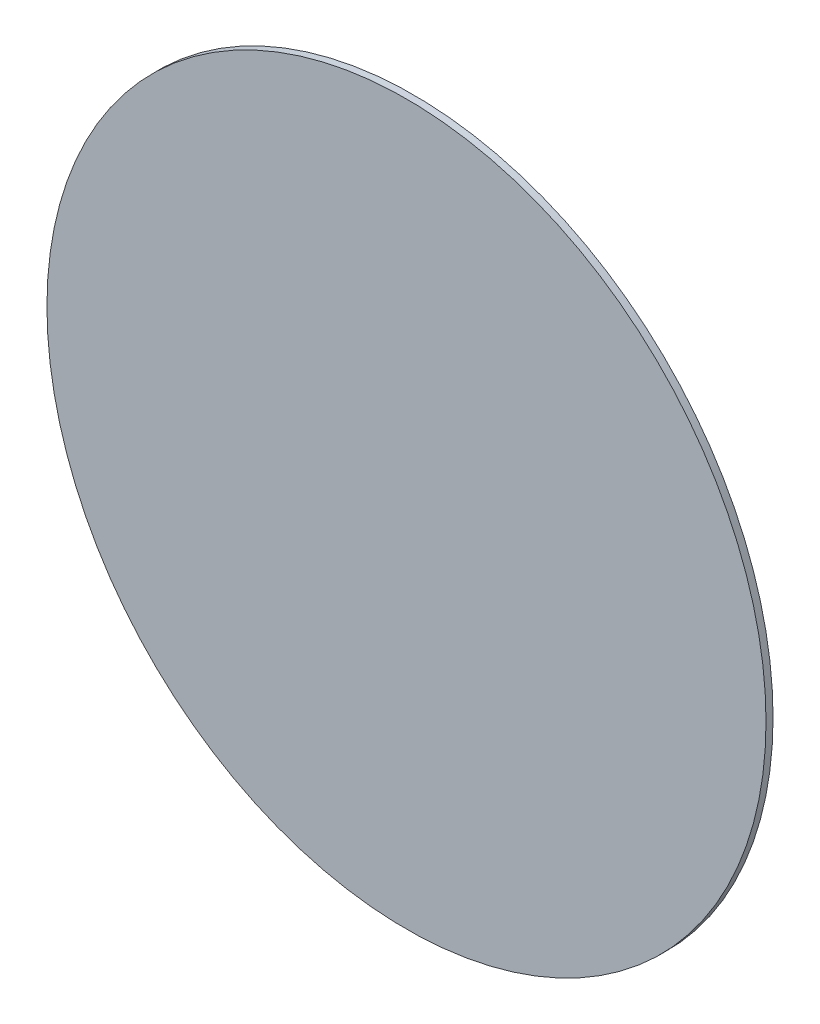
SolidWorks part; units mm, degrees
ref_plane "Plan de face" through (0, 0, 0) normal (0, 0, 1) x (1, 0, 0)
ref_plane "Plan de dessus" through (0, 0, 0) normal (0, 1, 0) x (1, 0, 0)
ref_plane "Plan de droite" through (0, 0, 0) normal (1, 0, 0) x (0, 0, -1)
sketch "Esquisse1" plane through (0, 0, 0) normal (0, 0, 1) x (1, 0, 0)
  circle A0 centre (0, 0) radius 13.3
  dimension "D1" = 26.6
extrude "Boss.-Extru.1" add sketch "Esquisse1" along normal blind 0.26
ref_plane "Plan1" through (0, 0, -0.125) normal (0, 0, -1) x (-1, 0, 0)
sketch "Esquisse2" [suppressed] plane through (0, 0, 0) normal (1, 0, 0) x (0, 0, -1)
  line L0 (0, -13.3) -> (0, 13.3) construction
  line L1 (0.125, -12.24) -> (0, -12.24) construction
  circle A0 centre (0.125, -12.115) radius 0.125
  dimension "D1" = 0.25
  dimension "D2" = 12.24
sketch "Esquisse4" plane through (0, 0, -0.125) normal (0, 0, -1) x (-1, 0, 0)
  circle A0 centre (0, 0) radius 12.115
  circle A1 centre (0, 0) radius 8.605 construction
  dimension "D1" = 24.23
  dimension "D2" = 17.21
curve "Hélice/Spirale1"
sweep "Balayage1" add path "Hélice/Spirale1" circular profile diameter 0.25 parameters "D3"=0.25
equation "\"D1@Esquisse4\"=24.48-0.25"
equation "\"D2@Esquisse4\"=16.96+0.25"
